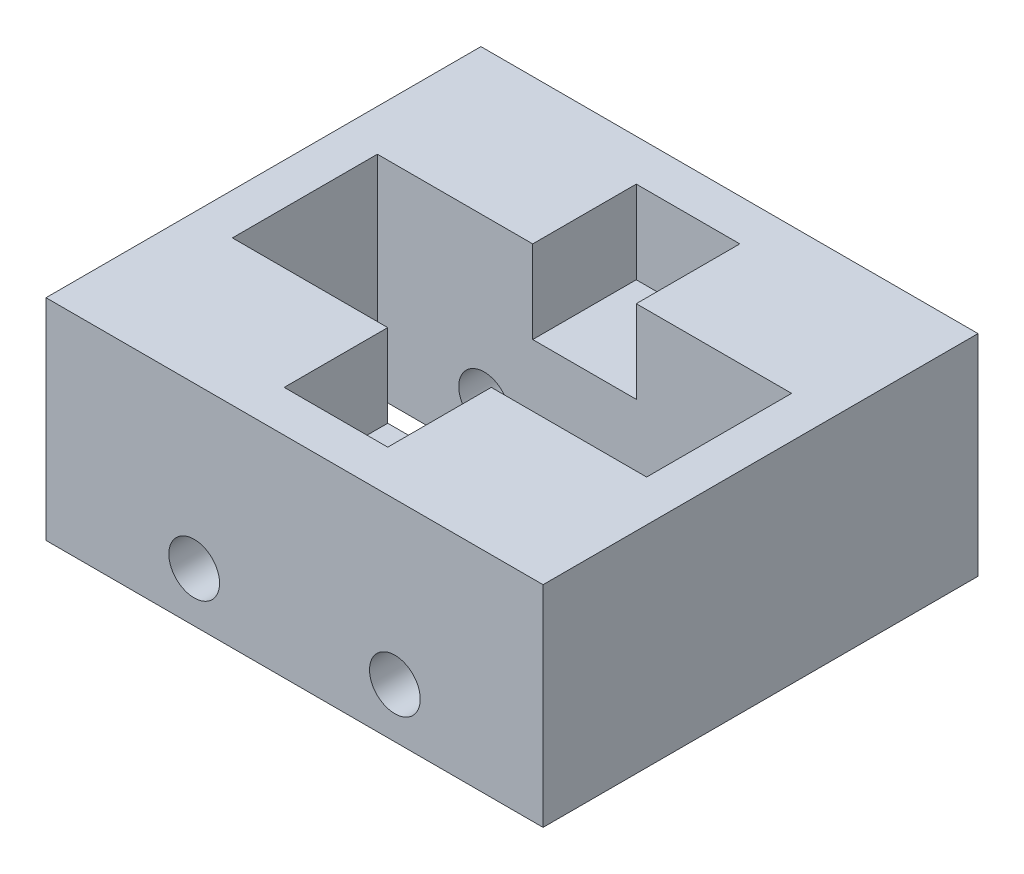
SolidWorks part; units mm, degrees
ref_plane "Plan de face" through (0, 0, 0) normal (0, 0, 1) x (1, 0, 0)
ref_plane "Plan de dessus" through (0, 0, 0) normal (0, 1, 0) x (1, 0, 0)
ref_plane "Plan de droite" through (0, 0, 0) normal (1, 0, 0) x (0, 0, -1)
sketch "Esquisse2" plane through (0, 0, 0) normal (0, 0, 1) x (1, 0, 0)
  line L0 (0, 5.075) -> (0, -5.075) construction
  line L1 (12, -5.075) -> (-12, -5.075)
  line L2 (12, -5.075) -> (12, 5.075)
  line L3 (12, 5.075) -> (2.5, 5.075)
  line L4 (-12, -5.075) -> (-12, 5.075)
  line L5 (12, -5.075) -> (-12, 5.075) construction
  line L6 (12, 5.075) -> (-12, -5.075) construction
  line L7 (-4.845, -2.675) -> (0, -2.675) construction
  line L8 (0, -2.675) -> (4.845, -2.675) construction
  line L9 (-2.5, 5.075) -> (-12, 5.075)
  line L11 (-2.5, 5.075) -> (-2.5, 1.075)
  line L12 (-2.5, 1.075) -> (2.5, 1.075)
  line L13 (2.5, 5.075) -> (2.5, 1.075)
  line L14 (-2.5, 5.075) -> (2.5, 5.075)
  circle A0 centre (-4.845, -2.675) radius 1.225
  circle A1 centre (4.845, -2.675) radius 1.225
  point P0 (0, 0)
  point P10 (0, 1.075)
  dimension "D3" = 2.45
  dimension "D4" = 2.4
  dimension "D1" = 10.15
  dimension "D2" = 24
  dimension "D5" = 9.69
  dimension "D6" = 4
  dimension "D7" = 5
extrude "Boss.-Extru.1" add sketch "Esquisse2" along normal blind 7 contours L3 L13 L12 L11 L9 L4 L1 L2 A1 A0
sketch "Esquisse3" plane through (0, 0, 7) normal (0, 0, 1) x (1, 0, 0)
  line L0 (-2.5, 5.075) -> (2.5, 5.075)
  line L1 (2.5, 5.075) -> (2.5, 1.075)
  line L2 (2.5, 1.075) -> (-2.5, 1.075)
  line L3 (-2.5, 1.075) -> (-2.5, 5.075)
extrude "Boss.-Extru.2" add sketch "Esquisse3" against normal blind 2 contours L0 L1 L2 L3
sketch "Esquisse5" plane through (0, 0, 0) normal (0, 0, -1) x (-1, 0, 0)
  line L0 (-12, -5.075) -> (12, -5.075) construction
  line L1 (-12, 5.075) -> (-10, 5.075)
  line L2 (-12, 5.075) -> (-12, -5.075)
  line L3 (-12, -5.075) -> (-10, -5.075)
  line L4 (-10, 5.075) -> (-10, -5.075)
  line L5 (12, 5.075) -> (10, 5.075)
  line L6 (12, 5.075) -> (12, -5.075)
  line L7 (12, -5.075) -> (10, -5.075)
  line L8 (10, 5.075) -> (10, -5.075)
  dimension "D1" = 2
  dimension "D3" = 2
extrude "Boss.-Extru.3" add sketch "Esquisse5" along normal blind 7
ref_plane "Plan1" through (0, 0, -3.5) normal (0, 0, -1) x (-1, 0, 0)
mirror "Symétrie1" about plane through (0, 0, -3.5) normal (0, 0, -1) of bodies 103
